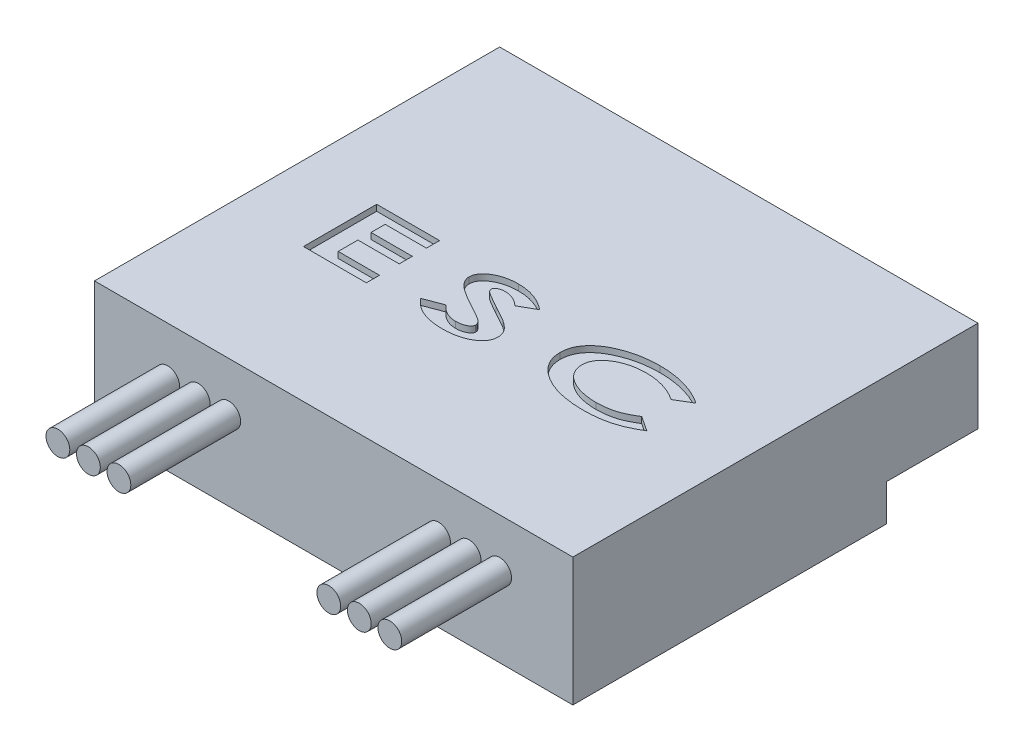
SolidWorks part; units mm, degrees
ref_plane "Front Plane" through (0, 0, 0) normal (0, 0, 1) x (1, 0, 0)
ref_plane "Top Plane" through (0, 0, 0) normal (0, 1, 0) x (1, 0, 0)
ref_plane "Right Plane" through (0, 0, 0) normal (1, 0, 0) x (0, 0, -1)
sketch "Sketch1" plane through (0, 0, 0) normal (0, 1, 0) x (1, 0, 0)
  line L1 (0, 0) -> (78.4, 0)
  line L2 (0, 0) -> (0, 66.4)
  line L3 (0, 66.4) -> (78.4, 66.4)
  line L4 (78.4, 0) -> (78.4, 66.4)
  dimension "D1" = 78.4
  dimension "D2" = 66.4
extrude "Boss-Extrude1" add sketch "Sketch1" along normal blind 21
sketch "Sketch2" plane through (0, 0, 0) normal (0, 0, 1) x (1, 0, 0)
  line L0 (0, 21) -> (0, 0) construction
  line L1 (0, 21) -> (78.4, 21) construction
  line L2 (39.2, 21) -> (39.2, 0) construction
  line L3 (0, 0) -> (78.4, 0) construction
  circle A0 centre (17, 13) radius 1.95
  circle A1 centre (12, 13) radius 1.95
  circle A2 centre (22, 13) radius 1.95
  circle A3 centre (56.4, 13) radius 1.95
  circle A4 centre (61.4, 13) radius 1.95
  circle A5 centre (66.4, 13) radius 1.95
  dimension "D1" = 3.9
  dimension "D2" = 12
  dimension "D3" = 5
  dimension "D4" = 5
  dimension "D5" = 8
extrude "Boss-Extrude2" add sketch "Sketch2" along normal blind 18
sketch "Sketch3" plane through (0, 0, 0) normal (0, -1, 0) x (1, 0, 0)
  line L0 (0, -66.4) -> (0, 0) construction
  line L1 (20, -51.4) -> (52, -51.4)
  line L2 (20, -51.4) -> (20, -31.4)
  line L3 (20, -31.4) -> (52, -31.4)
  line L4 (52, -51.4) -> (52, -31.4)
  line L5 (78.4, -66.4) -> (0, -66.4) construction
  dimension "D1" = 20
  dimension "D2" = 15
  dimension "D3" = 20
  dimension "D4" = 32
extrude "Cut-Extrude1" cut sketch "Sketch3" against normal blind 10
sketch "Sketch4" plane through (0, 0, 0) normal (0, -1, 0) x (1, 0, 0)
  line L0 (78.4, 0) -> (78.4, -66.4) construction
  line L1 (0, -66.4) -> (78.4, -66.4)
  line L2 (0, -66.4) -> (0, -51.4)
  line L3 (0, -51.4) -> (78.4, -51.4)
  line L4 (78.4, -66.4) -> (78.4, -51.4)
  dimension "D1" = 15
extrude "Cut-Extrude2" cut sketch "Sketch4" against normal blind 6
sketch "Sketch5" plane through (0, 10, 0) normal (0, -1, 0) x (1, 0, 0)
  line L2 (52, -31.4) -> (20, -31.4) construction
  line L3 (52, -51.4) -> (52, -31.4) construction
  circle A0 centre (49.05, -34.35) radius 1.95
  circle A1 centre (34.15, -34.35) radius 1.95
  dimension "D1" = 14.9
  dimension "D2" = 3.9
  dimension "D3" = 3.9
  dimension "D4" = 2.95
  dimension "D5" = 2.95
extrude "Boss-Extrude6" add sketch "Sketch5" along normal blind 9
sketch "Sketch6" plane through (0, 21, 0) normal (0, 1, 0) x (1, 0, 0)
  line L0 (0, 22) -> (78.4, 22) construction
  line L1 (0, 66.4) -> (0, 0) construction
  line L2 (78.4, 0) -> (78.4, 66.4) construction
  line L3 (0, 0) -> (78.4, 0) construction
  text T0 "<b>ESC</b>" font "Century Gothic" height 12
  dimension "D1" = 22
extrude "Cut-Extrude3" cut sketch "Sketch6" against normal blind 1
